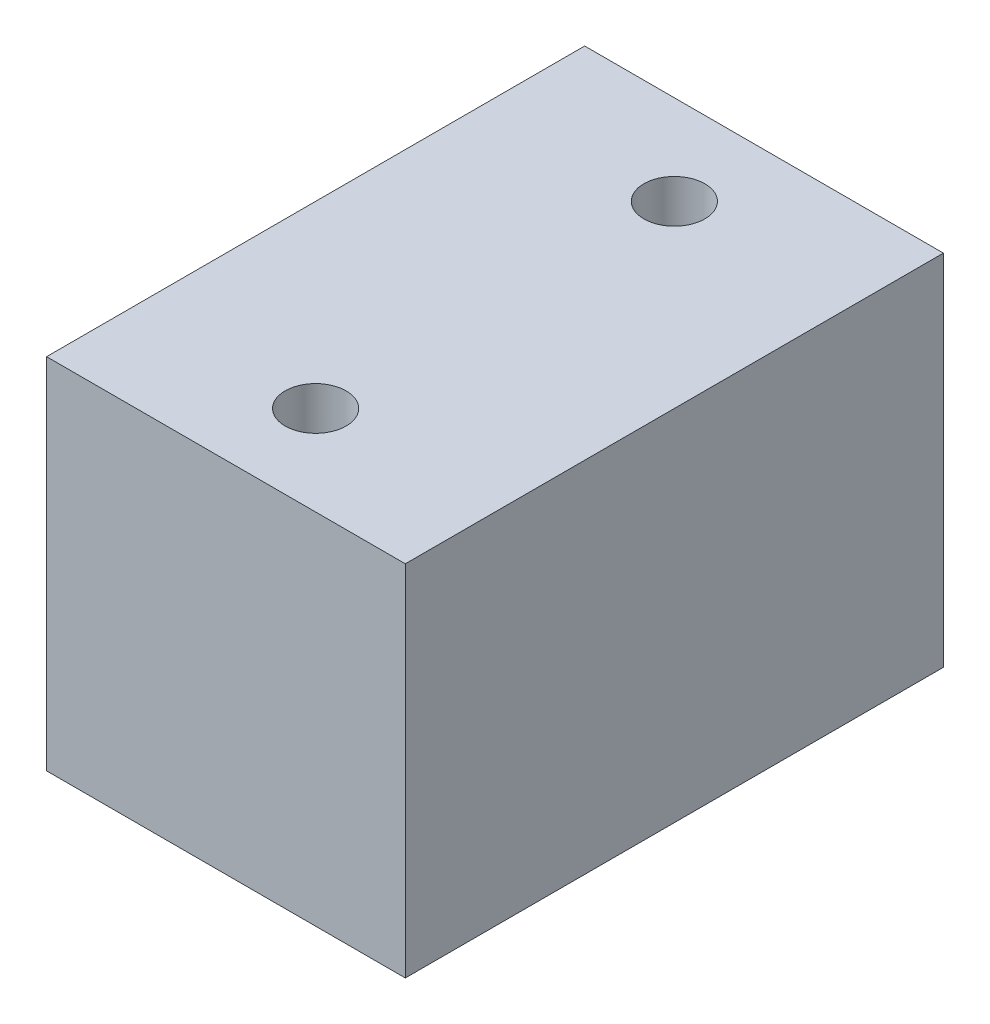
SolidWorks part; units mm, degrees
ref_plane "前视基准面" through (0, 0, 0) normal (0, 0, 1) x (1, 0, 0)
ref_plane "上视基准面" through (0, 0, 0) normal (0, 1, 0) x (1, 0, 0)
ref_plane "右视基准面" through (0, 0, 0) normal (1, 0, 0) x (0, 0, -1)
other "Configuration Table"
sketch "草图1" plane through (0, 0, 0) normal (0, 0, 1) x (1, 0, 0)
  line L1 (-10, 10) -> (10, 10)
  line L2 (-10, 10) -> (-10, -10)
  line L3 (-10, -10) -> (10, -10)
  line L4 (10, 10) -> (10, -10)
  line L5 (-10, 10) -> (10, -10) construction
  line L6 (-10, -10) -> (10, 10) construction
  point P0 (0, 0)
  dimension "D1" = 20
  dimension "D2" = 20
extrude "凸台-拉伸1" add sketch "草图1" along normal blind 30
sketch "草图2" plane through (0, 10, 0) normal (0, 1, 0) x (1, 0, 0)
  line L0 (0, 0) -> (0, -30) construction
  line L1 (10, -30) -> (-10, -30) construction
  circle A1 centre (0, -5) radius 1.7
  circle A2 centre (0, -25) radius 1.7
  dimension "D1" = 3.4
  dimension "D2" = 20
  dimension "D3" = 5
extrude "切除-拉伸1" cut sketch "草图2" against normal blind 30
